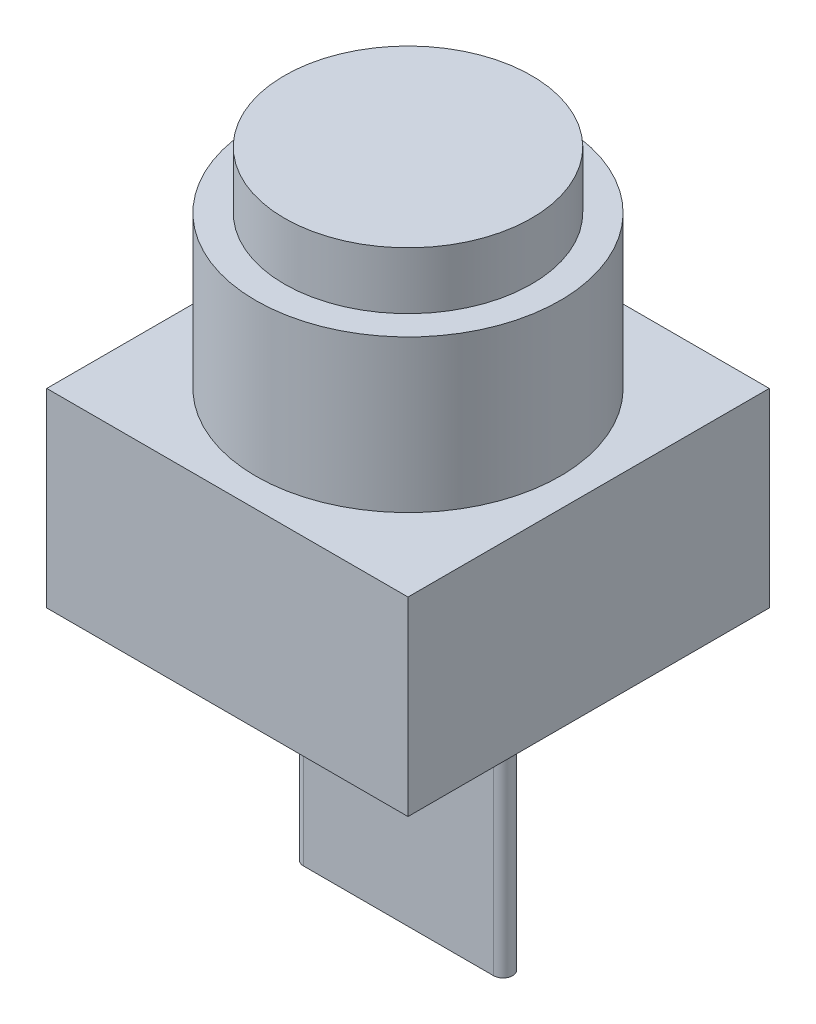
SolidWorks part; units mm, degrees
ref_plane "Front Plane" through (0, 0, 0) normal (0, 0, 1) x (1, 0, 0)
ref_plane "Top Plane" through (0, 0, 0) normal (0, 1, 0) x (1, 0, 0)
ref_plane "Right Plane" through (0, 0, 0) normal (1, 0, 0) x (0, 0, -1)
sketch "Sketch2" plane through (0, 0, 0) normal (0, 1, 0) x (1, 0, 0)
  line L1 (-4.75, -4.75) -> (4.75, -4.75)
  line L2 (-4.75, -4.75) -> (-4.75, 4.75)
  line L3 (-4.75, 4.75) -> (4.75, 4.75)
  line L4 (4.75, -4.75) -> (4.75, 4.75)
  line L5 (-4.75, -4.75) -> (4.75, 4.75) construction
  line L6 (-4.75, 4.75) -> (4.75, -4.75) construction
  point P0 (0, 0)
  dimension "D1" = 9.5
  dimension "D2" = 9.5
extrude "Boss-Extrude1" add sketch "Sketch2" along normal blind 5
sketch "Sketch3" plane through (0, 5, 0) normal (0, 1, 0) x (1, 0, 0)
  circle A0 centre (0, 0) radius 4
  point P2 (0, 0)
  dimension "D1" = 8
extrude "Boss-Extrude2" add sketch "Sketch3" along normal blind 4
sketch "Sketch4" plane through (0, 9, 0) normal (0, 1, 0) x (1, 0, 0)
  circle A0 centre (0, 0) radius 3.25
  dimension "D1" = 6.5
extrude "Boss-Extrude3" add sketch "Sketch4" along normal blind 1.5
sketch "Sketch5" plane through (0, 0, 0) normal (0, -1, 0) x (1, 0, 0)
  line L0 (-2.5, 0) -> (2.5, 0) construction
  line L1 (-2.5, -0.25) -> (2.5, -0.25)
  line L2 (-2.5, 0.25) -> (2.5, 0.25)
  arc A0 (-2.5, -0.25) -> (-2.5, 0.25) centre (-2.5, 0) cw
  arc A1 (2.5, -0.25) -> (2.5, 0.25) centre (2.5, 0) ccw
  point P3 (3.859, 0)
  point P4 (0, 0)
  dimension "D1" = 5
  dimension "D2" = 0.25
  dimension "D3" = 0.25
extrude "Boss-Extrude4" add sketch "Sketch5" along normal blind 7
